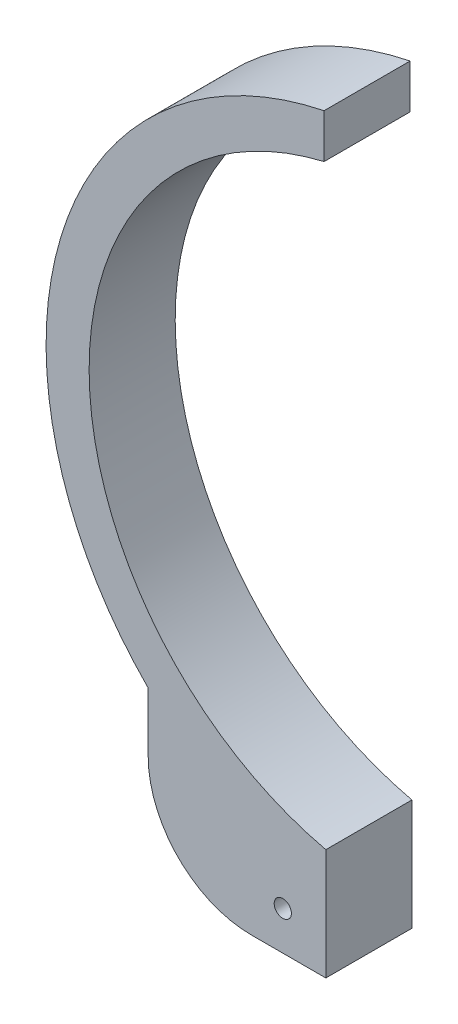
SolidWorks part; units mm, degrees
ref_plane "Front Plane" through (0, 0, 0) normal (0, 0, 1) x (1, 0, 0)
ref_plane "Top Plane" through (0, 0, 0) normal (0, 1, 0) x (1, 0, 0)
ref_plane "Right Plane" through (0, 0, 0) normal (1, 0, 0) x (0, 0, -1)
sketch "Sketch1" plane through (0, 0, 0) normal (0, 0, 1) x (1, 0, 0)
  line L0 (0, -35.5) -> (0, 35.5)
  line L1 (0, 35.5) -> (0, 40.5)
  line L2 (0, 40.5) -> (0, -40.5)
  line L3 (-28.6378, -28.6378) -> (-28.6378, -40.5)
  line L4 (-28.6378, -40.5) -> (0, -40.5)
  line L5 (-0.6378, -40.5) -> (-0.6378, -35.4943)
  line L6 (-3.6378, -40.5) -> (-3.6378, -35.3131)
  line L7 (-3.6378, -40.5) -> (-3.6378, -47.5)
  line L8 (-28.6378, -40.5) -> (0, -40.5)
  line L9 (-28.6378, -40.5) -> (-28.6378, -35.5)
  line L10 (-16.6378, -47.5) -> (0, -47.5)
  line L11 (0, -40.5) -> (0, -47.5)
  line L12 (-8, -34.5868) -> (-8, -47.5)
  line L13 (-13, -38.3569) -> (-13, -47.5)
  circle A0 centre (0, 0) radius 35.5
  circle A1 centre (0, 0) radius 40.5
  arc A2 (-40.5, 0) -> (0, -40.5) centre (0, 0) ccw
  arc A3 (-28.6378, -28.6378) -> (0, -40.5) centre (0, 0) ccw
  arc A4 (-28.6378, -35.5) -> (-16.6378, -47.5) centre (-16.6378, -35.5) ccw
  circle A5 centre (-13, -42.9999) radius 1
  point P27 (-28.6378, -47.5)
  dimension "D1" = 71
  dimension "D4" = 28
  dimension "D5" = 2
  dimension "D8" = 5
  dimension "D9" = 7
  dimension "D11" = 12
  dimension "D2" = 5
  dimension "D3" = 5
  dimension "D6" = 13
  dimension "D7" = 25
  dimension "D10" = 4.643
extrude "Boss-Extrude1" add sketch "Sketch1" along normal blind 10
sketch "Sketch2" plane through (0, 0, 10) normal (0, 0, 1) x (1, 0, 0)
  line L1 (0, 40.5) -> (-8.204, 40.5)
  line L2 (0, 40.5) -> (0, 31.1468)
  line L3 (0, 31.1468) -> (-8.204, 31.1468)
  line L4 (-8.204, 40.5) -> (-8.204, 31.1468)
extrude "Cut-Extrude1" cut sketch "Sketch2" against normal blind 10
